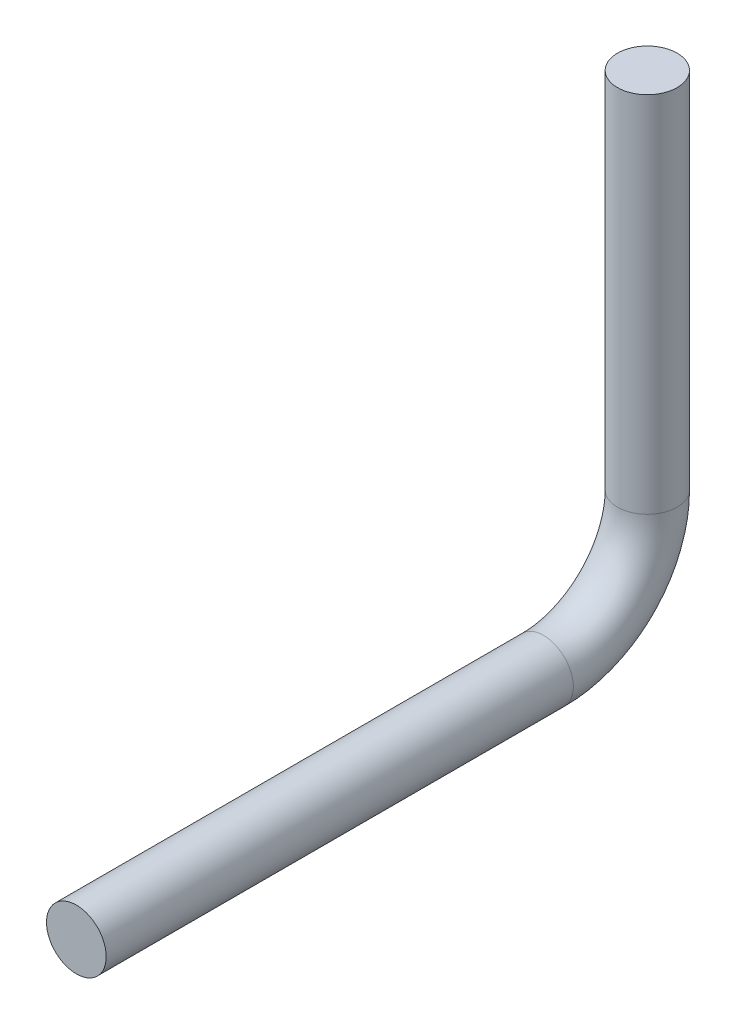
SolidWorks part; units mm, degrees
ref_plane "Front Plane" through (0, 0, 0) normal (0, 0, 1) x (1, 0, 0)
ref_plane "Top Plane" through (0, 0, 0) normal (0, 1, 0) x (1, 0, 0)
ref_plane "Right Plane" through (0, 0, 0) normal (1, 0, 0) x (0, 0, -1)
sketch "Sketch1" plane through (0, 0, 0) normal (1, 0, 0) x (0, 0, -1)
  line L0 (-139.7, 0) -> (-25.4, 0)
  line L1 (0, 25.4) -> (0, 114.3)
  arc A0 (-25.4, 0) -> (0, 25.4) centre (-25.4, 25.4) ccw
  point P6 (0, 0)
  dimension "D3" = 25.4
  dimension "D1" = 139.7
  dimension "D2" = 114.3
ref_plane "Plane1" through (0, 0, 139.7) normal (0, 0, 1) x (1, 0, 0)
sketch "Sketch2" plane through (0, 0, 139.7) normal (0, 0, 1) x (1, 0, 0)
  circle A0 centre (0, 0) radius 7.3025
  dimension "D1" = 14.605
sweep "Sweep1" add profiles "Sketch2" path "Sketch1"
sketch "Sketch3" plane through (0, 0, 0) normal (0, 0, 1) x (1, 0, 0)
  line L0 (0, 114.3) -> (0, 25.4) construction
  line L1 (7.3025, 114.3) -> (-7.3025, 114.3) construction
  line L2 (7.3025, 25.4) -> (-7.3025, 25.4) construction
  circle A0 centre (0, 101.6) radius 4.699
  circle A1 centre (0, 38.1) radius 4.699
  dimension "D1" = 9.398
  dimension "D2" = 12.7
  dimension "D3" = 12.7
